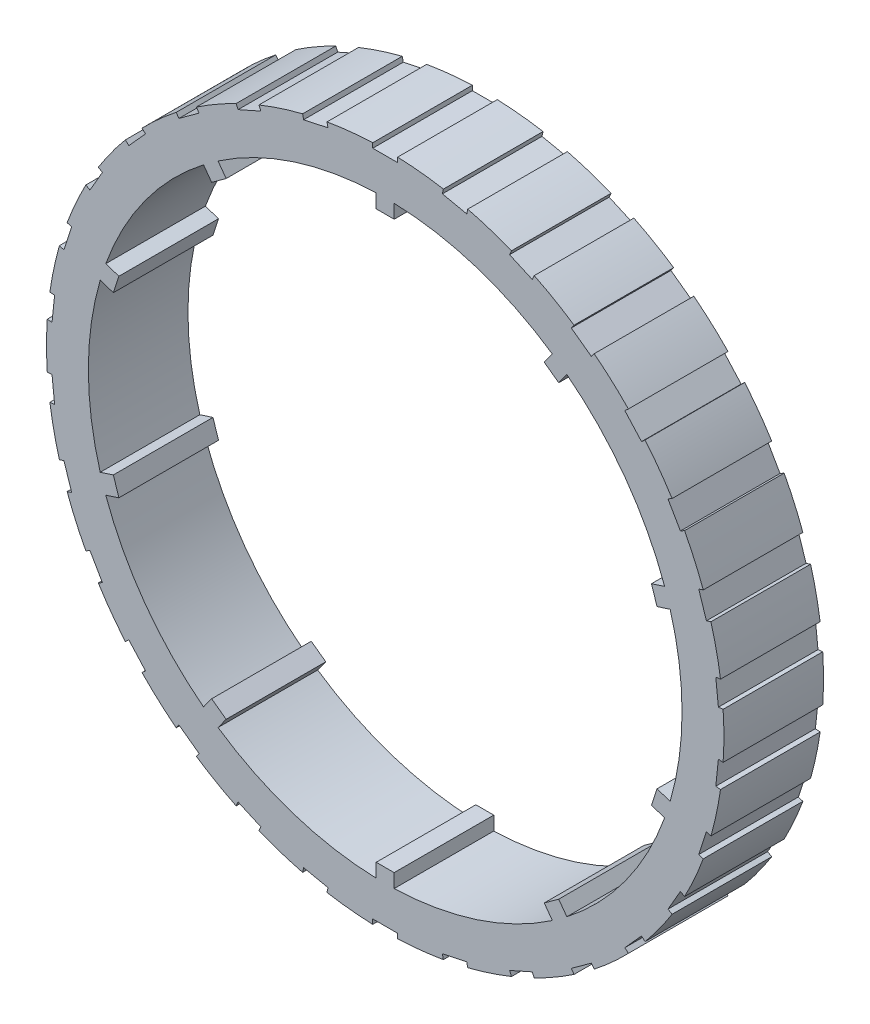
SolidWorks part; units mm, degrees
ref_plane "Front Plane" through (0, 0, 0) normal (0, 0, 1) x (1, 0, 0)
ref_plane "Top Plane" through (0, 0, 0) normal (0, 1, 0) x (1, 0, 0)
ref_plane "Right Plane" through (0, 0, 0) normal (1, 0, 0) x (0, 0, -1)
sketch "Sketch2" plane through (0, 0, 0) normal (0, 0, 1) x (1, 0, 0)
  circle A0 centre (0, 0) radius 34
  dimension "D1" = 68
extrude "Boss-Extrude1" add sketch "Sketch2" along normal blind 10 contours A0
sketch "Sketch3" plane through (0, 0, 0) normal (0, 0, 1) x (1, 0, 0)
  line L0 (0, 0) -> (-29.8, 0) construction
  line L1 (0, 0) -> (0, 29.8) construction
  circle A3 centre (0, 0) radius 29.8
  point P0 (0, 0)
  dimension "D1" = 59.6
extrude "Cut-Extrude1" cut sketch "Sketch3" along normal through all
sketch "Sketch4" plane through (0, 0, 0) normal (0, 0, 1) x (1, 0, 0)
  line L0 (0, 29.8) -> (0, 0) construction
  line L1 (-0.9, 28.4) -> (0.9, 28.4)
  line L2 (-0.9, 28.4) -> (-0.9, 31.2)
  line L3 (-0.9, 31.2) -> (0.9, 31.2)
  line L4 (0.9, 28.4) -> (0.9, 31.2)
  line L5 (-0.9, 28.4) -> (0.9, 31.2) construction
  line L6 (-0.9, 31.2) -> (0.9, 28.4) construction
  circle A0 centre (0, 0) radius 29.8 construction
  point P0 (0, 29.8)
  dimension "D1" = 1.8
  dimension "D2" = 2.8
extrude "Boss-Extrude2" add sketch "Sketch4" along normal up to surface (10 mm away) up to face at (29.8, 0, 10)
pattern_circular "CirPattern1" count 10 over 360 about axis through (0, 0, 0) along (0, 0, 1) of "Boss-Extrude2"
sketch "Sketch5" plane through (0, 0, 0) normal (0, 0, 1) x (1, 0, 0)
  line L0 (0, 34) -> (0, 0) construction
  line L1 (-1.25, 33.5) -> (1.25, 33.5)
  line L2 (-1.25, 33.5) -> (-1.25, 34.5)
  line L3 (-1.25, 34.5) -> (1.25, 34.5)
  line L4 (1.25, 33.5) -> (1.25, 34.5)
  line L5 (-1.25, 33.5) -> (1.25, 34.5) construction
  line L6 (-1.25, 34.5) -> (1.25, 33.5) construction
  circle A0 centre (0, 0) radius 34 construction
  point P0 (0, 34)
  dimension "D1" = 2.5
  dimension "D2" = 1
ref_plane "Plane1" through (0, 0, 5) normal (0, 0, 1) x (1, 0, 0)
extrude "Cut-Extrude2" cut sketch "Sketch5" along normal through all
pattern_circular "CirPattern3" count 30 over 360 about axis through (0, 0, 0) along (0, 0, 1) of "Cut-Extrude2"
